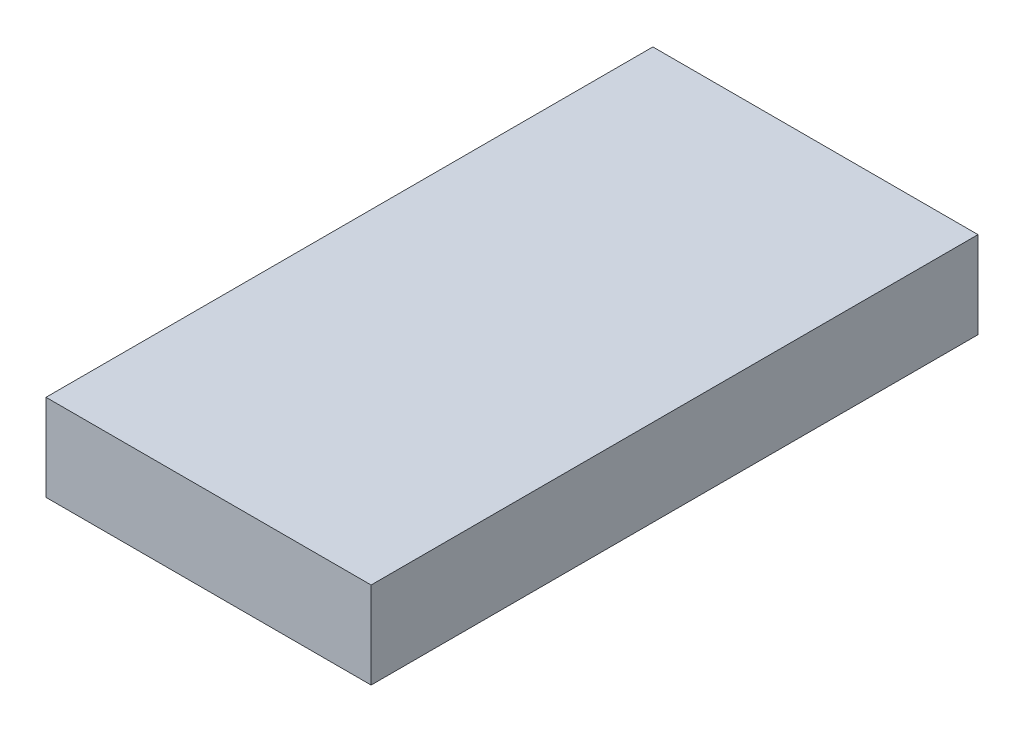
SolidWorks part; units mm, degrees
ref_plane "Front Plane" through (0, 0, 0) normal (0, 0, 1) x (1, 0, 0)
ref_plane "Top Plane" through (0, 0, 0) normal (0, 1, 0) x (1, 0, 0)
ref_plane "Right Plane" through (0, 0, 0) normal (1, 0, 0) x (0, 0, -1)
sketch "Sketch1" plane through (0, 0, 0) normal (0, 1, 0) x (1, 0, 0)
  line L1 (75, -140) -> (-75, -140)
  line L2 (75, -140) -> (75, 140)
  line L3 (75, 140) -> (-75, 140)
  line L4 (-75, -140) -> (-75, 140)
  line L5 (75, -140) -> (-75, 140) construction
  line L6 (75, 140) -> (-75, -140) construction
  point P0 (0, 0)
  dimension "D1" = 150
  dimension "D2" = 280
extrude "Boss-Extrude1" add sketch "Sketch1" along normal blind 40
